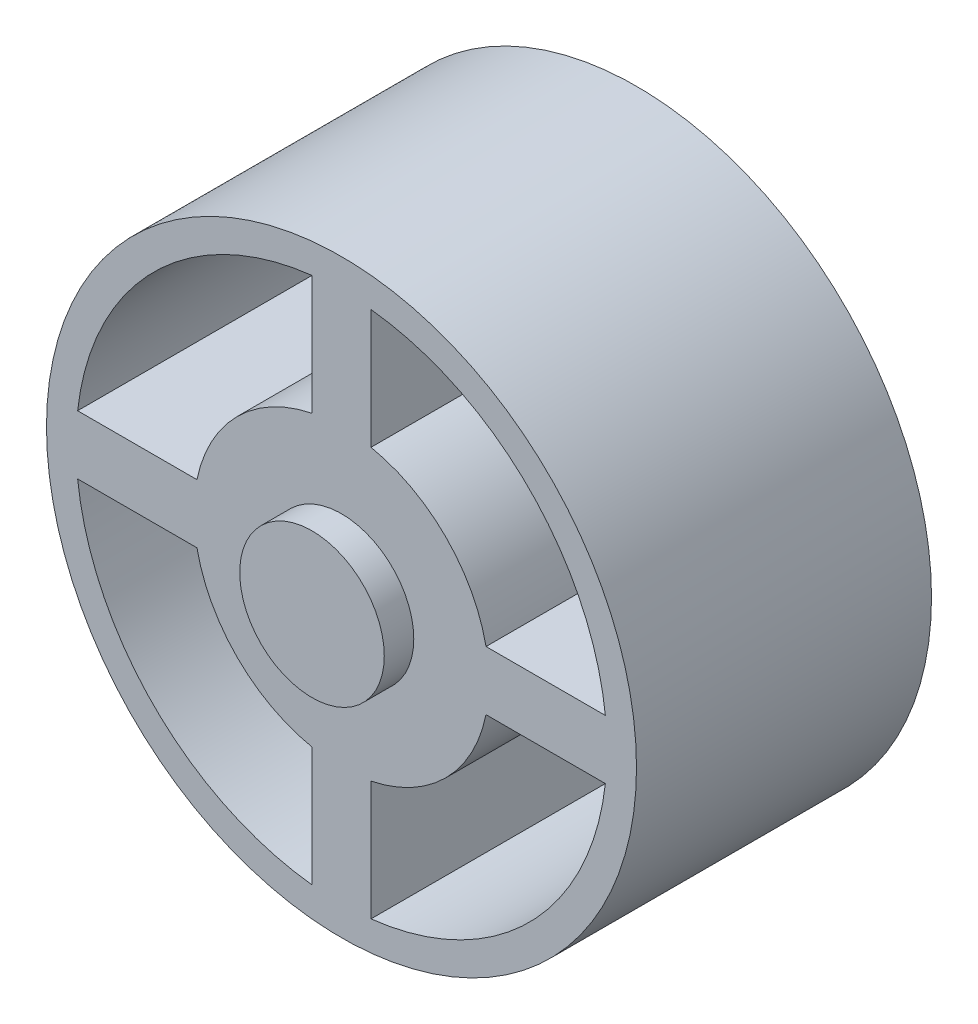
SolidWorks part; units mm, degrees
material "6061-T6 (SS)"
ref_plane "Front Plane" through (0, 0, 0) normal (0, 0, 1) x (1, 0, 0)
ref_plane "Top Plane" through (0, 0, 0) normal (0, 1, 0) x (1, 0, 0)
ref_plane "Right Plane" through (0, 0, 0) normal (1, 0, 0) x (0, 0, -1)
sketch "Sketch1" plane through (0, 0, 0) normal (0, 0, 1) x (1, 0, 0)
  line L6 (-10, 89.4427) -> (-10, 48.9898)
  line L7 (10, 89.4427) -> (10, 48.9898)
  line L8 (89.4427, 10) -> (48.9898, 10)
  line L9 (89.4427, -10) -> (48.9898, -10)
  line L10 (10, -89.4427) -> (10, -48.9898)
  line L11 (-10, -89.4427) -> (-10, -48.9898)
  line L12 (-89.4427, -10) -> (-48.9898, -10)
  line L13 (-89.4427, 10) -> (-48.9898, 10)
  circle A0 centre (0, 0) radius 100
  arc A2 (-10, 48.9898) -> (-48.9898, 10) centre (0, 0) ccw
  arc A3 (-10, 89.4427) -> (-89.4427, 10) centre (0, 0) ccw
  circle A5 centre (0, 0) radius 90 construction
  arc A9 (-89.4427, -10) -> (-10, -89.4427) centre (0, 0) ccw
  arc A10 (-48.9898, -10) -> (-10, -48.9898) centre (0, 0) ccw
  arc A11 (10, -48.9898) -> (48.9898, -10) centre (0, 0) ccw
  arc A12 (10, -89.4427) -> (89.4427, -10) centre (0, 0) ccw
  arc A13 (89.4427, 10) -> (10, 89.4427) centre (0, 0) ccw
  arc A14 (48.9898, 10) -> (10, 48.9898) centre (0, 0) ccw
  point P38 (0, 0)
  dimension "D1" = 200
  dimension "D5" = 20
  dimension "D4" = 10
  dimension "D7" = 4
extrude "Boss-Extrude1" add sketch "Sketch1" along normal blind 100
sketch "Sketch2" plane through (0, 0, 100) normal (0, 0, 1) x (1, 0, 0)
  circle A0 centre (0, 0) radius 24.5
  dimension "D1" = 49
extrude "Boss-Extrude2" add sketch "Sketch2" along normal blind 10 and the other way blind 110
